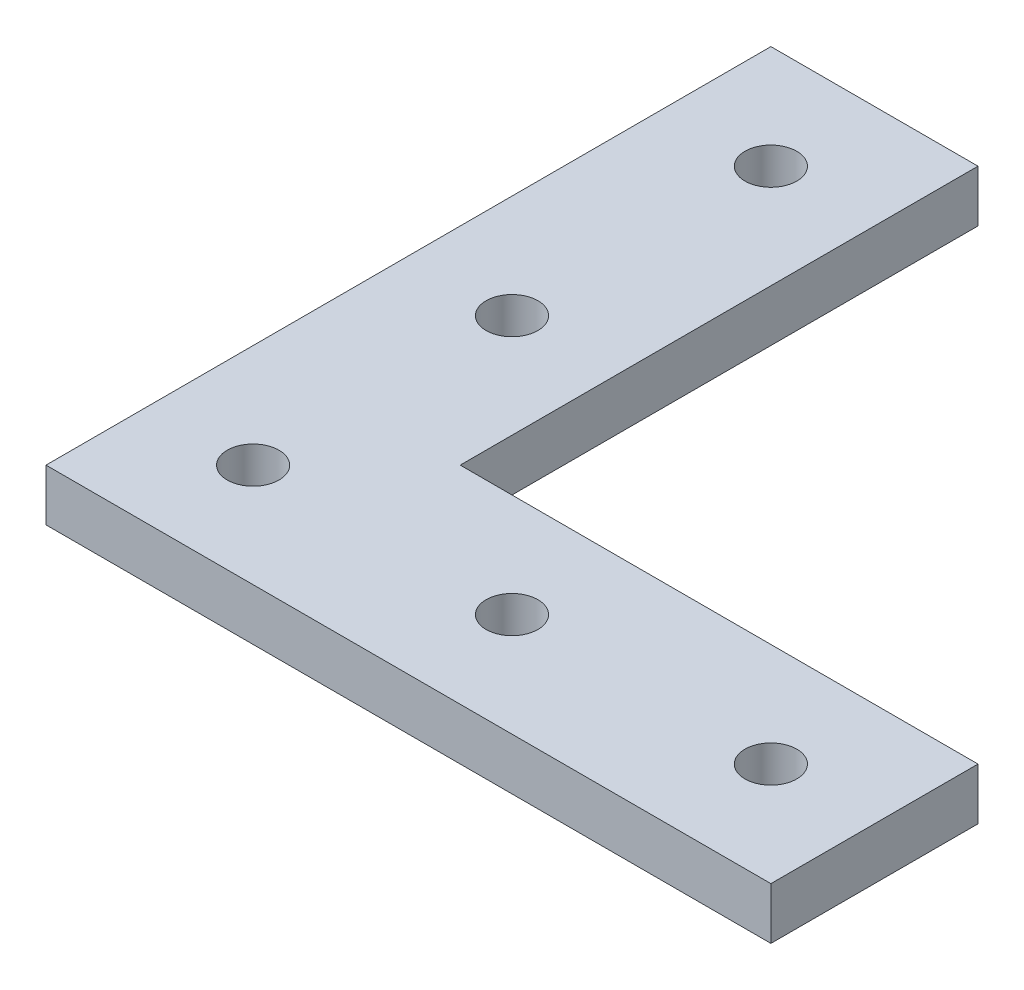
SolidWorks part; units mm, degrees
ref_plane "정면도" through (0, 0, 0) normal (0, 0, 1) x (1, 0, 0)
ref_plane "평면도" through (0, 0, 0) normal (0, 1, 0) x (1, 0, 0)
ref_plane "우측면도" through (0, 0, 0) normal (1, 0, 0) x (0, 0, -1)
sketch "스케치1" plane through (0, 0, 0) normal (0, 1, 0) x (1, 0, 0)
  line L0 (0, 0) -> (0, 70)
  line L1 (0, 70) -> (20, 70)
  line L2 (20, 70) -> (20, 20)
  line L3 (20, 20) -> (70, 20)
  line L4 (70, 20) -> (70, 0)
  line L5 (70, 0) -> (0, 0)
  dimension "D1" = 20
  dimension "D2" = 20
  dimension "D3" = 70
  dimension "D4" = 70
extrude "보스-돌출1" add sketch "스케치1" along normal blind 5
sketch "스케치2" plane through (0, 5, 0) normal (0, 1, 0) x (1, 0, 0)
  line L0 (0, 0) -> (70, 0) construction
  line L1 (20, 20) -> (20, 70) construction
  line L2 (0, 70) -> (0, 0) construction
  line L3 (20, 70) -> (0, 70) construction
  line L4 (70, 0) -> (70, 20) construction
  circle A0 centre (10, 60) radius 2.5
  circle A1 centre (10, 35) radius 2.5
  circle A2 centre (10, 10) radius 2.5
  circle A3 centre (35, 10) radius 2.5
  circle A4 centre (60, 10) radius 2.5
  dimension "D1" = 5
  dimension "D6" = 10
  dimension "D10" = 10
  dimension "D11" = 25
  dimension "D2" = 10
  dimension "D3" = 10
  dimension "D4" = 10
  dimension "D5" = 10
  dimension "D7" = 10
  dimension "D8" = 10
  dimension "D9" = 25
extrude "컷-돌출1" cut sketch "스케치2" against normal through all
